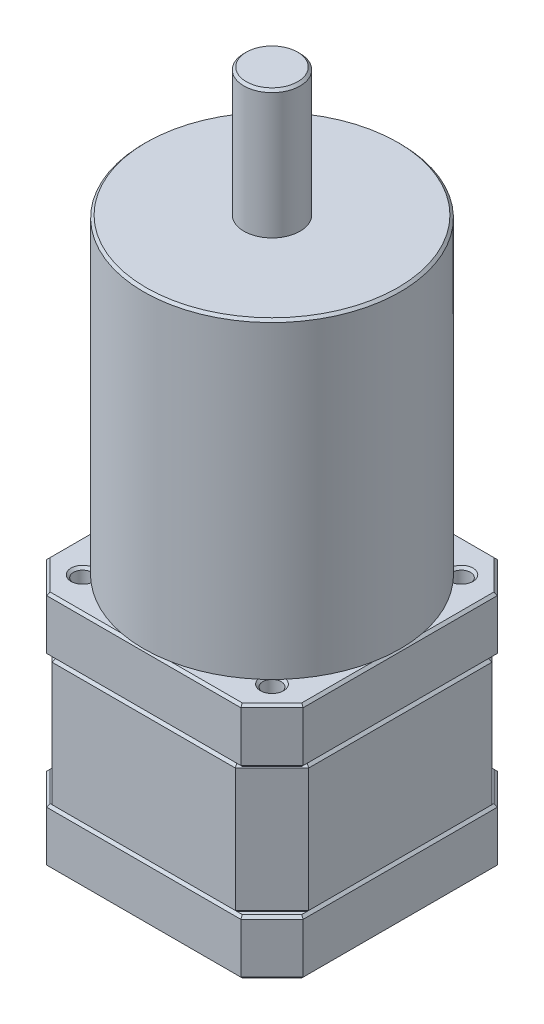
SolidWorks part; units mm, degrees
ref_plane "Front Plane" through (0, 0, 0) normal (0, 0, 1) x (1, 0, 0)
ref_plane "Top Plane" through (0, 0, 0) normal (0, 1, 0) x (1, 0, 0)
ref_plane "Right Plane" through (0, 0, 0) normal (1, 0, 0) x (0, 0, -1)
sketch "Sketch1" plane through (0, 0, 0) normal (0, 1, 0) x (1, 0, 0)
  line L1 (-21, -21) -> (21, -21)
  line L2 (-21, -21) -> (-21, 21)
  line L3 (-21, 21) -> (21, 21)
  line L4 (21, -21) -> (21, 21)
  line L5 (-21, -21) -> (21, 21) construction
  line L6 (-21, 21) -> (21, -21) construction
  point P0 (0, 0)
  dimension "D1" = 42
extrude "Boss-Extrude1" add sketch "Sketch1" along normal blind 9
chamfer "Chamfer1" distance 5.1 angle 45 4 edges at (-21, 4.5, -21) (21, 4.5, -21) (21, 4.5, 21) (-21, 4.5, 21)
chamfer "Chamfer2" distance 0.4 angle 45 16 edges at (-18.45, 0, 18.45) (0, 0, 21) (18.45, 0, 18.45) (21, 0, 0) (18.45, 0, -18.45) (0, 0, -21) (-18.45, 0, -18.45) (-21, 0, 0) (18.45, 9, -18.45) (21, 9, 0) (18.45, 9, 18.45) (0, 9, 21) (-18.45, 9, 18.45) (-21, 9, 0) (-18.45, 9, -18.45) (0, 9, -21)
sketch "Sketch3" plane through (0, 9, 0) normal (0, 1, 0) x (1, 0, 0)
  line L1 (21, 21) -> (-21, 21)
  line L2 (21, 21) -> (21, -21)
  line L3 (21, -21) -> (-21, -21)
  line L4 (-21, 21) -> (-21, -21)
  line L5 (21, 21) -> (-21, -21) construction
  line L6 (21, -21) -> (-21, 21) construction
  point P0 (0, 0)
  dimension "D1" = 42
extrude "Boss-Extrude3" add sketch "Sketch3" along normal blind 21 separate body
chamfer "Chamfer3" distance 6 angle 45 4 edges at (-21, 19.5, -21) (21, 19.5, -21) (-21, 19.5, 21) (21, 19.5, 21)
chamfer "Chamfer4" distance 0.4 angle 45 16 edges at (18, 30, -18) (21, 30, 0) (18, 30, 18) (0, 30, 21) (-18, 30, 18) (-21, 30, 0) (-18, 30, -18) (0, 30, -21) (-18, 9, 18) (0, 9, 21) (18, 9, 18) (21, 9, 0) (18, 9, -18) (0, 9, -21) (-18, 9, -18) (-21, 9, 0)
sketch "Sketch4" plane through (0, 30, 0) normal (0, 1, 0) x (1, 0, 0)
  line L1 (21, 21) -> (-21, 21)
  line L2 (21, 21) -> (21, -21)
  line L3 (21, -21) -> (-21, -21)
  line L4 (-21, 21) -> (-21, -21)
  line L5 (21, 21) -> (-21, -21) construction
  line L6 (21, -21) -> (-21, 21) construction
  point P0 (0, 0)
  dimension "D1" = 42
extrude "Boss-Extrude4" add sketch "Sketch4" along normal blind 9 separate body
chamfer "Chamfer5" distance 5.1 angle 45 4 edges at (21, 34.5, 21) (-21, 34.5, 21) (-21, 34.5, -21) (21, 34.5, -21)
sketch "Sketch5" plane through (0, 39, 0) normal (0, 1, 0) x (1, 0, 0)
  circle A0 centre (0, 0) radius 11
  dimension "D1" = 22
extrude "Boss-Extrude5" add sketch "Sketch5" along normal blind 2
sketch "Sketch7" plane through (0, 39, 0) normal (0, 1, 0) x (1, 0, 0)
  line L1 (15.5, 15.5) -> (-15.5, 15.5) construction
  line L2 (15.5, 15.5) -> (15.5, -15.5) construction
  line L3 (15.5, -15.5) -> (-15.5, -15.5) construction
  line L4 (-15.5, 15.5) -> (-15.5, -15.5) construction
  line L5 (15.5, 15.5) -> (-15.5, -15.5) construction
  line L6 (15.5, -15.5) -> (-15.5, 15.5) construction
  circle A0 centre (15.5, -15.5) radius 1.5
  circle A1 centre (-15.5, -15.5) radius 1.5
  circle A2 centre (15.5, 15.5) radius 1.5
  circle A3 centre (-15.5, 15.5) radius 1.5
  point P0 (0, 0)
  dimension "D2" = 3
  dimension "D1" = 31
extrude "Cut-Extrude1" cut sketch "Sketch7" against normal blind 5
chamfer "Chamfer6" distance 0.4 angle 45 26 edges at (-18.45, 39, 18.45) (-21, 39, 0) (-18.45, 39, -18.45) (0, 39, -21) (18.45, 39, -18.45) (21, 39, 0) (18.45, 39, 18.45) (0, 39, 21) (18.45, 30, -18.45) (0, 30, -21) (-18.45, 30, -18.45) (-21, 30, 0) (-18.45, 30, 18.45) (0, 30, 21) (18.45, 30, 18.45) (21, 30, 0) (0, 39, 11) (0, 41, 11) (15.5, 39, 17) (-15.5, 39, -14) (15.5, 39, -14) (-15.5, 39, 17) (-15.5, 34, 17) (-15.5, 34, -14) (15.5, 34, -14) (15.5, 34, 17)
sketch "Sketch6" plane through (0, 41, 0) normal (0, 1, 0) x (1, 0, 0)
  circle A0 centre (0, 0) radius 2.5
  dimension "D1" = 5
extrude "Boss-Extrude6" add sketch "Sketch6" along normal blind 24 separate body
chamfer "Chamfer7" distance 0.4 angle 45 1 edges at (0, 65, 2.5)
sketch "Sketch8" plane through (0, 39, 0) normal (0, 1, 0) x (1, 0, 0)
  circle A0 centre (0, 0) radius 21
  dimension "D1" = 42
extrude "Boss-Extrude7" add sketch "Sketch8" along normal blind 51
sketch "Sketch9" plane through (0, 90, 0) normal (0, 1, 0) x (1, 0, 0)
  circle A0 centre (0, 0) radius 4.6
  dimension "D1" = 9.2
extrude "Boss-Extrude8" add sketch "Sketch9" along normal blind 21 separate body
chamfer "Chamfer8" distance 0.4 angle 45 1 edges at (0, 111, 4.6)
chamfer "Chamfer9" distance 0.4 angle 45 1 edges at (0, 90, 21)
